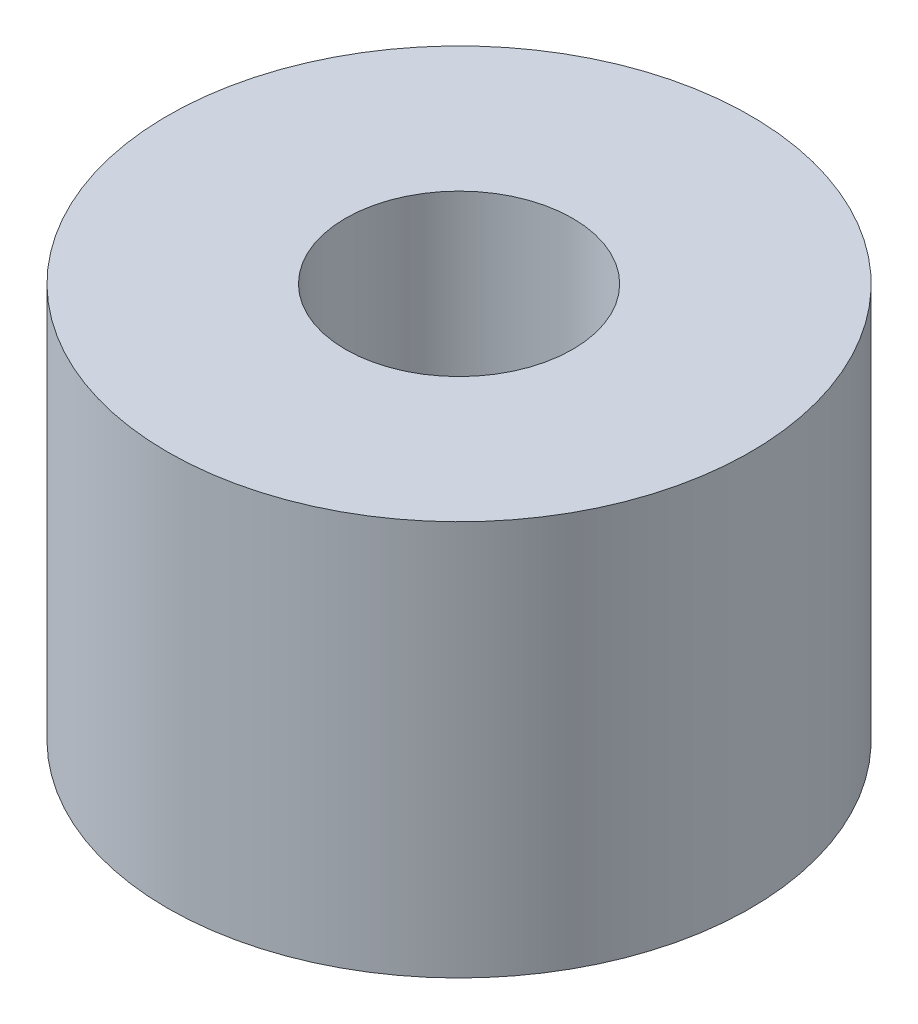
SolidWorks part; units mm, degrees
ref_plane "Front" through (0, 0, 0) normal (0, 0, 1) x (1, 0, 0)
ref_plane "Top" through (0, 0, 0) normal (0, 1, 0) x (1, 0, 0)
ref_plane "Right" through (0, 0, 0) normal (1, 0, 0) x (0, 0, -1)
sketch "Sketch1" plane through (0, 0, 0) normal (0, 1, 0) x (1, 0, 0)
  circle A0 centre (0, 0) radius 2.95
  circle A1 centre (0, 0) radius 1.15
  dimension "D1" = 5.9
  dimension "D2" = 1.8
extrude "Boss-Extrude1" add sketch "Sketch1" along normal blind 4
sketch "Sketch2" plane through (0, 0, 0) normal (1, 0, 0) x (0, 0, -1)
  line L0 (0, 0) -> (0, 19.5733)
